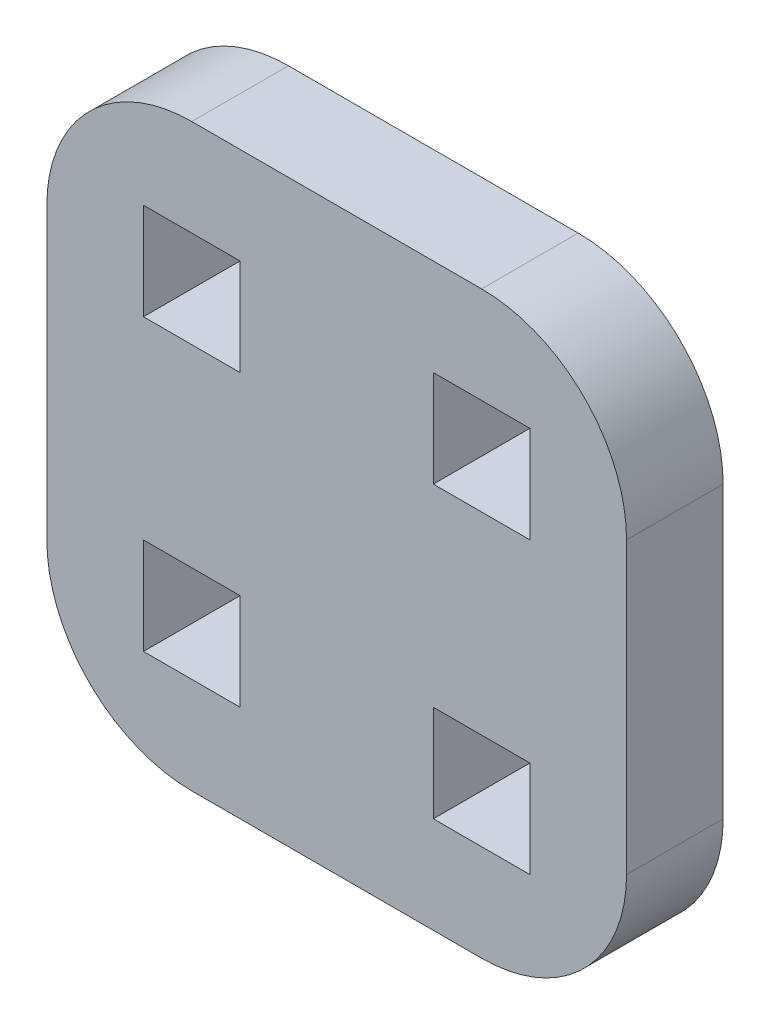
SolidWorks part; units mm, degrees
ref_plane "Alzado" through (0, 0, 0) normal (0, 0, 1) x (1, 0, 0)
ref_plane "Planta" through (0, 0, 0) normal (0, 1, 0) x (1, 0, 0)
ref_plane "Vista lateral" through (0, 0, 0) normal (1, 0, 0) x (0, 0, -1)
sketch "Model" plane through (0, 0, 0) normal (0, 0, 1) x (1, 0, 0)
  line L0 (8.3216, 296.5404) -> (8.3216, 293.5404)
  line L1 (11.3216, 296.5404) -> (8.3216, 296.5404)
  line L2 (11.3216, 293.5404) -> (11.3216, 296.5404)
  line L3 (8.3216, 293.5404) -> (11.3216, 293.5404)
  line L4 (17.3216, 296.5404) -> (17.3216, 293.5404)
  line L5 (20.3216, 296.5404) -> (17.3216, 296.5404)
  line L6 (20.3216, 293.5404) -> (20.3216, 296.5404)
  line L7 (17.3216, 293.5404) -> (20.3216, 293.5404)
  line L8 (8.3216, 287.5404) -> (8.3216, 284.5404)
  line L9 (11.3216, 287.5404) -> (8.3216, 287.5404)
  line L10 (11.3216, 284.5404) -> (11.3216, 287.5404)
  line L11 (8.3216, 284.5404) -> (11.3216, 284.5404)
  line L12 (17.3216, 287.5404) -> (17.3216, 284.5404)
  line L13 (20.3216, 287.5404) -> (17.3216, 287.5404)
  line L14 (20.3216, 284.5404) -> (20.3216, 287.5404)
  line L15 (17.3216, 284.5404) -> (20.3216, 284.5404)
  line L16 (9.8216, 299.5404) -> (18.8216, 299.5404)
  line L17 (9.8216, 281.5404) -> (18.8216, 281.5404)
  line L18 (5.3216, 295.0404) -> (5.3216, 286.0404)
  line L19 (23.3216, 295.0404) -> (23.3216, 286.0404)
  arc A0 (23.3216, 295.0404) -> (18.8216, 299.5404) centre (18.8216, 295.0404) ccw
  arc A1 (18.8216, 281.5404) -> (23.3216, 286.0404) centre (18.8216, 286.0404) ccw
  arc A2 (9.8216, 299.5404) -> (5.3216, 295.0404) centre (9.8216, 295.0404) ccw
  arc A3 (5.3216, 286.0404) -> (9.8216, 281.5404) centre (9.8216, 286.0404) ccw
extrude "Saliente-Extruir1" add sketch "Model" along normal blind 3
